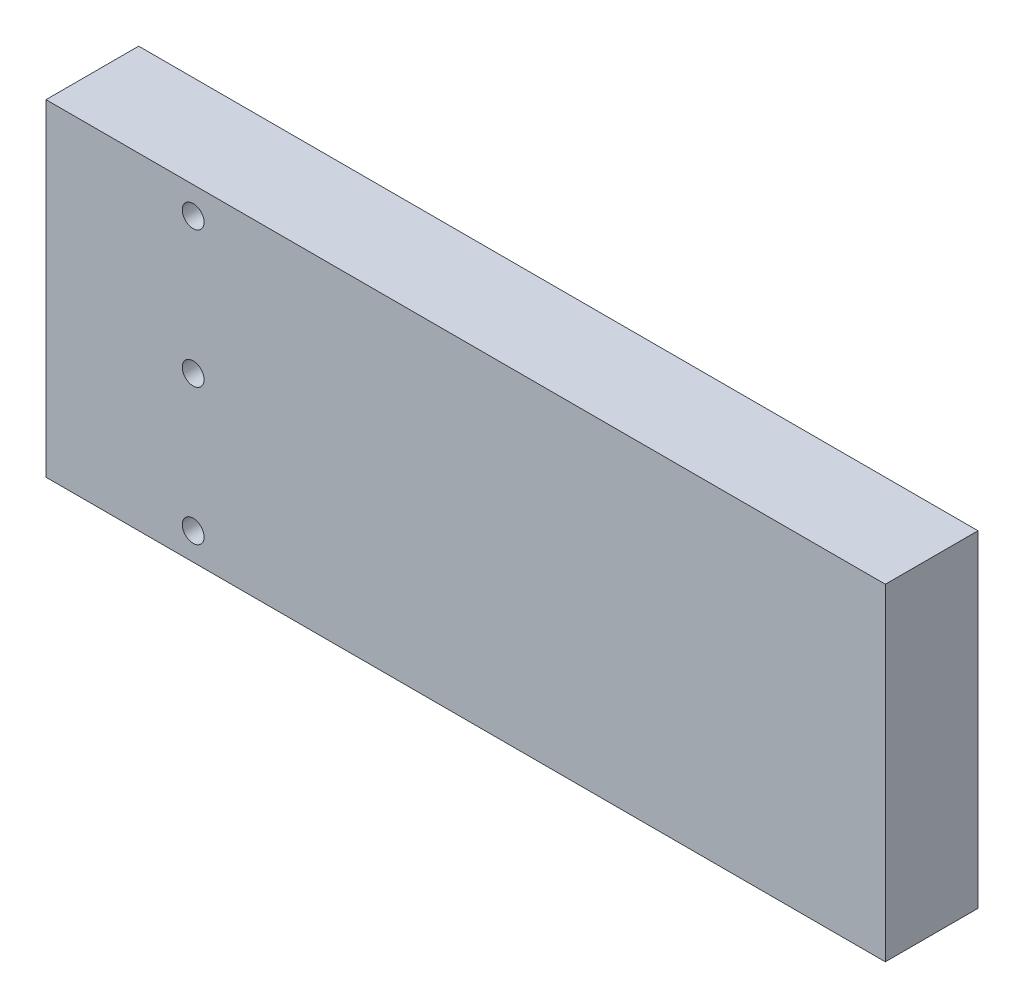
SolidWorks part; units mm, degrees
ref_plane "Plan de face" through (0, 0, 0) normal (0, 0, 1) x (1, 0, 0)
ref_plane "Plan de dessus" through (0, 0, 0) normal (0, 1, 0) x (1, 0, 0)
ref_plane "Plan de droite" through (0, 0, 0) normal (1, 0, 0) x (0, 0, -1)
sketch "Esquisse1" plane through (0, 0, 0) normal (0, 0, 1) x (1, 0, 0)
  line L1 (0, 0) -> (54, 0)
  line L2 (0, 0) -> (0, -60)
  line L3 (0, -60) -> (54, -60)
  line L4 (54, 0) -> (54, -60)
  line L5 (54, 0) -> (100, 0)
  line L6 (54, 0) -> (54, -60)
  line L7 (54, -60) -> (100, -60)
  line L8 (100, 0) -> (100, -60)
  line L9 (100, -60) -> (154, -60)
  line L10 (100, -60) -> (100, 0)
  line L11 (100, 0) -> (154, 0)
  line L12 (154, -60) -> (154, 0)
  circle A0 centre (27, -55) radius 2
  circle A1 centre (27, -30) radius 2
  circle A2 centre (27, -5) radius 2
  point P11 (27, 0)
  dimension "D1" = 4
  dimension "D2" = 4
  dimension "D3" = 4
  dimension "D4" = 60
  dimension "D5" = 54
  dimension "D6" = 0
  dimension "D7" = 0
  dimension "D8" = 0
  dimension "D9" = 30
  dimension "D10" = 5
  dimension "D11" = 5
  dimension "D12" = 54
  dimension "D13" = 100
extrude "Boss.-Extru.1" add sketch "Esquisse1" along normal blind 17 contours L4 L1 L2 L3 A2 A1 A0 | L8 L5 L4 L7 | L9 L12 L11 L8
